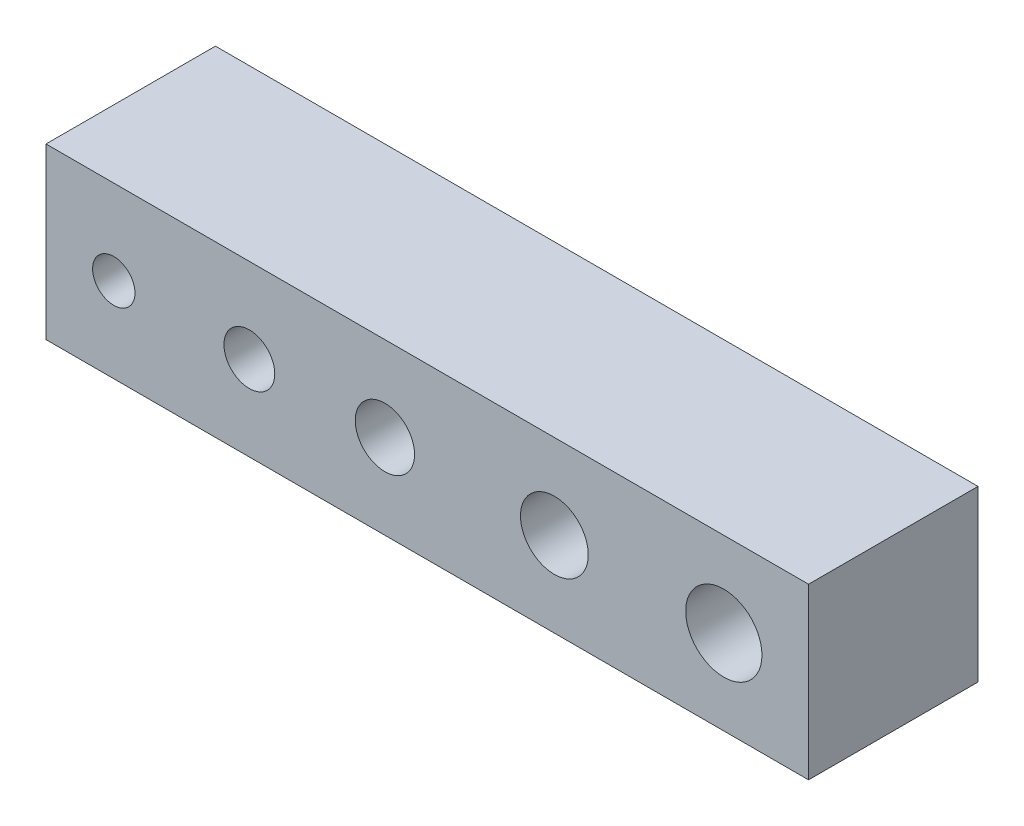
SolidWorks part; units mm, degrees
ref_plane "Front Plane" through (0, 0, 0) normal (0, 0, 1) x (1, 0, 0)
ref_plane "Top Plane" through (0, 0, 0) normal (0, 1, 0) x (1, 0, 0)
ref_plane "Right Plane" through (0, 0, 0) normal (1, 0, 0) x (0, 0, -1)
sketch "Sketch1" plane through (0, 0, 0) normal (0, 0, 1) x (1, 0, 0)
  line L1 (0, 0) -> (-45, 0)
  line L2 (0, 0) -> (0, -10)
  line L3 (0, -10) -> (-45, -10)
  line L4 (-45, 0) -> (-45, -10)
  dimension "D1" = 45
  dimension "D2" = 10
extrude "Boss-Extrude1" add sketch "Sketch1" along normal blind 10
sketch "Sketch2" plane through (0, 0, 10) normal (0, 0, 1) x (1, 0, 0)
  line L0 (-45, 0) -> (-45, -10) construction
  circle A0 centre (-41, -5) radius 1.25
  circle A1 centre (-33, -5) radius 1.5
  circle A2 centre (-25, -5) radius 1.75
  circle A3 centre (-15, -5) radius 2
  circle A4 centre (-5, -5) radius 2.25
  point P12 (-45, -5)
  dimension "D1" = 0
  dimension "D2" = 0
  dimension "D3" = 0
  dimension "D4" = 0
  dimension "D5" = 0
  dimension "D6" = 4
  dimension "D7" = 8
  dimension "D8" = 8
  dimension "D9" = 10
  dimension "D10" = 10
  dimension "D11" = 2.5
  dimension "D12" = 3
  dimension "D13" = 3.5
  dimension "D14" = 4
  dimension "D15" = 4.5
extrude "Cut-Extrude1" cut sketch "Sketch2" against normal blind 16
